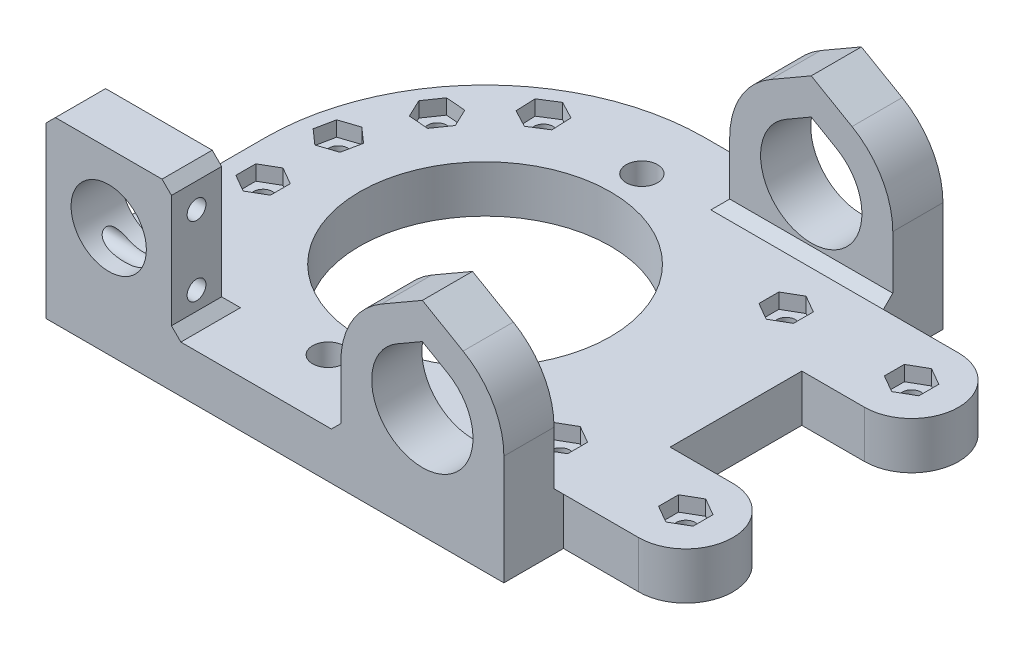
SolidWorks part; units mm, degrees
ref_plane "Front Plane" through (0, 0, 0) normal (0, 0, 1) x (1, 0, 0)
ref_plane "Top Plane" through (0, 0, 0) normal (0, 1, 0) x (1, 0, 0)
ref_plane "Right Plane" through (0, 0, 0) normal (1, 0, 0) x (0, 0, -1)
sketch "Sketch1" plane through (0, 0, 0) normal (0, 1, 0) x (1, 0, 0)
  line L0 (-62.4163, 0) -> (61.9965, 0) construction
  line L1 (-36.5, 35) -> (36.5, 35)
  line L2 (-36.5, 35) -> (-36.5, -35)
  line L3 (-36.5, -35) -> (36.5, -35)
  line L4 (36.5, 35) -> (36.5, -35) construction
  line L5 (-36.5, 35) -> (36.5, -35) construction
  line L6 (-36.5, -35) -> (36.5, 35) construction
  line L7 (36.5, 35) -> (36.5, 25.5)
  line L8 (36.5, 25.5) -> (48.5, 25.5)
  line L9 (48.5, 10.5) -> (38.5, 10.5)
  line L10 (38.5, 10.5) -> (38.5, -10.5)
  line L11 (48.5, -10.5) -> (38.5, -10.5)
  line L12 (36.5, -25.5) -> (48.5, -25.5)
  line L13 (36.5, -35) -> (36.5, -25.5)
  arc A0 (48.5, 25.5) -> (48.5, 10.5) centre (48.5, 18) cw
  arc A1 (48.5, -25.5) -> (48.5, -10.5) centre (48.5, -18) ccw
  point P0 (0, 0)
  point P15 (38.5, 0)
  dimension "D1" = 73
  dimension "D2" = 70
  dimension "D3" = 75
  dimension "D4" = 15
  dimension "D5" = 10
  dimension "D6" = 9.5
extrude "Boss-Extrude1" add sketch "Sketch1" along normal blind 7.5
sketch "Sketch3" plane through (0, 0, 35) normal (0, 0, 1) x (1, 0, 0)
  line L0 (36.5, 7.5) -> (36.5, 0) construction
  line L1 (36.5, 7.5) -> (10.5, 7.5)
  line L2 (36.5, 7.5) -> (36.5, 17.5)
  line L3 (36.5, 17.5) -> (10.5, 17.5) construction
  line L4 (10.5, 7.5) -> (10.5, 17.5)
  line L5 (-36.5, 7.5) -> (36.5, 7.5) construction
  line L6 (-36.5, 0) -> (36.5, 0) construction
  line L7 (23.5, 17.5) -> (23.5, 40.9913) construction
  line L8 (17, 28.7583) -> (23.5, 32.5111)
  line L9 (19.4625, 24.4932) -> (23.5, 26.8242)
  line L10 (17, 28.7583) -> (23.5, 17.5) construction
  line L11 (27.5375, 24.4932) -> (23.5, 26.8242)
  line L12 (30, 28.7583) -> (23.5, 32.5111)
  arc A0 (19.4625, 24.4932) -> (27.5375, 24.4932) centre (23.5, 17.5) ccw
  arc A1 (10.5, 17.5) -> (17, 28.7583) centre (23.5, 17.5) cw
  arc A2 (30, 28.7583) -> (36.5, 17.5) centre (23.5, 17.5) cw
  point P10 (23.5, 17.5)
  dimension "D3" = 16.15
  dimension "D1" = 26
  dimension "D2" = 17.5
  dimension "D4" = 120
extrude "Boss-Extrude3" add sketch "Sketch3" against normal blind 8
mirror "Mirror1" about plane through (0, 0, 0) normal (0, 0, 1) of "Boss-Extrude3"
sketch "Sketch10" plane through (0, 0, 0) normal (0, -1, 0) x (1, 0, 0)
  line L1 (-36.5, 27) -> (-16.5, 27)
  line L2 (-36.5, 27) -> (-36.5, 35)
  line L3 (-36.5, 35) -> (-16.5, 35)
  line L4 (-16.5, 27) -> (-16.5, 35)
  line L6 (-36.5, 35) -> (36.5, 35) construction
  line L7 (31.575, 35) -> (15.425, 35) construction
  point P9 (23.5, 35)
  point P14 (-26.5, 35)
  dimension "D1" = 8
  dimension "D4" = 50
extrude "Boss-Extrude4" add sketch "Sketch10" against normal offset from surface (28.5 mm away) 21 up to face at (22.7812, 7.5, -0.2031) offset beyond the face yes
sketch "Sketch11" plane through (0, 0, 35) normal (0, 0, 1) x (1, 0, 0)
  circle A0 centre (-26.5, 17.5) radius 6
  point P2 (23.5, 17.5)
  dimension "D1" = 12
  dimension "D2" = 50
extrude "Cut-Extrude6" cut sketch "Sketch11" against normal up to next
sketch "Sketch12" plane through (-36.5, 0, 0) normal (-1, 0, 0) x (0, 0, 1)
  line L0 (27, 17.5) -> (35, 17.5) construction
  line L1 (27, 28.5) -> (27, 7.5) construction
  line L2 (35, 28.5) -> (35, 0) construction
  line L3 (27, 23.5) -> (27, 11.5) construction
  circle A0 centre (31, 23.05) radius 1.5
  circle A1 centre (31, 11.95) radius 1.5
  point P12 (31, 21.55)
  point P13 (31, 13.45)
  point P14 (31, 17.5)
  dimension "D2" = 3
  dimension "D1" = 8.1
extrude "Cut-Extrude7" cut sketch "Sketch12" against normal up to next
sketch "Sketch6" plane through (0, 0, 0) normal (0, -1, 0) x (1, 0, 0)
  line L0 (-36.5, -35) -> (-36.5, 35) construction
  line L3 (-36.5, 35) -> (36.5, 35) construction
  line L5 (-20.5, 35) -> (-32.5, 35) construction
  line L6 (31.575, 35) -> (15.425, 35) construction
  line L7 (-26.5, 35) -> (23.5, 35) construction
  line L9 (-1.5, 35) -> (-1.5, 0) construction
  circle A0 centre (-1.5, 0) radius 20
  point P3 (-26.5, 35)
  point P5 (-36.5, 0)
  point P10 (23.5, 35)
  point P18 (-1.5, 35)
  dimension "D1" = 40
extrude "Cut-Extrude3" cut sketch "Sketch6" against normal through all
sketch "Sketch15" plane through (0, 0, 0) normal (0, -1, 0) x (1, 0, 0)
  line L0 (-1.5, 35) -> (-1.5, -35) construction
  line L1 (-36.5, 35) -> (36.5, 35) construction
  line L2 (36.5, -35) -> (-36.5, -35) construction
  line L3 (-21.5, 0) -> (18.5, 0) construction
  circle A1 centre (-1.5, 0) radius 20 construction
  circle A2 centre (-1.5, 25) radius 2.5
  circle A3 centre (-1.5, -25) radius 2.5
  point P8 (-1.5, 0)
  dimension "D1" = 5
  dimension "D2" = 25
extrude "Cut-Extrude9" cut sketch "Sketch15" against normal through all
sketch "Sketch14" plane through (0, 0, 0) normal (0, -1, 0) x (1, 0, 0)
  line L0 (0, 0) -> (89.7656, 0) construction
  line L1 (38.5, -10.5) -> (38.5, -25.5333) construction
  circle A0 centre (48.5, -18) radius 1.5
  circle A1 centre (28.5, -18) radius 1.5
  circle A2 centre (48.5, 18) radius 1.5
  circle A3 centre (28.5, 18) radius 1.5
  dimension "D1" = 3
  dimension "D2" = 20
extrude "Cut-Extrude8" cut sketch "Sketch14" against normal through all
sketch "Sketch19" plane through (0, 7.5, 0) normal (0, 1, 0) x (1, 0, 0)
  line L0 (38.5, 0) -> (82.8981, 0) construction
  line L1 (38.5, -10.5) -> (38.5, 10.5) construction
  line L2 (28.5, -18) -> (48.5, -18) construction
  line L3 (38.5, -18) -> (38.5, 0) construction
  line L4 (25.75, -16.4123) -> (28.5, -14.8246)
  line L5 (48.5, -14.8246) -> (45.75, -16.4123)
  line L6 (45.75, -16.4123) -> (45.75, -19.5877)
  line L7 (45.75, -19.5877) -> (48.5, -21.1754)
  line L8 (48.5, -21.1754) -> (51.25, -19.5877)
  line L9 (51.25, -19.5877) -> (51.25, -16.4123)
  line L10 (51.25, -16.4123) -> (48.5, -14.8246)
  line L11 (25.75, -19.5877) -> (25.75, -16.4123)
  line L12 (28.5, -21.1754) -> (25.75, -19.5877)
  line L13 (31.25, -19.5877) -> (28.5, -21.1754)
  line L14 (31.25, -16.4123) -> (31.25, -19.5877)
  line L15 (28.5, -14.8246) -> (31.25, -16.4123)
  line L16 (48.5, 21.1754) -> (51.25, 19.5877)
  line L17 (45.75, 19.5877) -> (48.5, 21.1754)
  line L18 (51.25, 16.4123) -> (48.5, 14.8246)
  line L19 (51.25, 19.5877) -> (51.25, 16.4123)
  line L20 (45.75, 16.4123) -> (45.75, 19.5877)
  line L21 (48.5, 14.8246) -> (45.75, 16.4123)
  line L22 (28.5, 14.8246) -> (31.25, 16.4123)
  line L23 (31.25, 16.4123) -> (31.25, 19.5877)
  line L24 (31.25, 19.5877) -> (28.5, 21.1754)
  line L25 (28.5, 21.1754) -> (25.75, 19.5877)
  line L26 (25.75, 19.5877) -> (25.75, 16.4123)
  line L27 (25.75, 16.4123) -> (28.5, 14.8246)
  circle A0 centre (48.5, -18) radius 2.75 construction
  circle A1 centre (48.5, 18) radius 2.75 construction
  dimension "D1" = 5.5
extrude "Cut-Extrude13" cut sketch "Sketch19" against normal blind 2.4
fillet "Fillet2" radius 35 1 edges at (-36.5, 3.75, -35)
chamfer "Chamfer2" distance 1.5 angle 45 8 edges at (-16.5, 28.5, 31) (-36.5, 28.5, 31) (-26.5, 7.5, 27) (-16.5, 7.5, 31) (23.5, 7.5, -27) (10.5, 7.5, -31)
sketch "Sketch17" plane through (0, 0, 0) normal (0, -1, 0) x (1, 0, 0)
  line L0 (-1.5, 0) -> (-36.5, 0) construction
  line L1 (-1.5, 0) -> (-16.5, -25.9808) construction
  line L2 (-1.5, 0) -> (-27.4808, 15) construction
  line L3 (-26.1909, 17.04) -> (-30.8939, 6) construction
  line L4 (-30.8939, 6) -> (-30.8939, -6) construction
  line L5 (-30.8939, -6) -> (-26.1909, -17.04) construction
  line L6 (-26.1909, -17.04) -> (-17.5373, -25.3536) construction
  line L7 (-30.8939, 6) -> (-30.8939, 18) construction
  circle A0 centre (-1.5, 0) radius 30 construction
  circle A1 centre (-30.8939, 6) radius 1.5
  circle A2 centre (-30.8939, -6) radius 1.5
  circle A3 centre (-30.8939, 18) radius 1.5
  circle A4 centre (-26.1909, -17.04) radius 1.5
  circle A5 centre (-17.5373, -25.3536) radius 1.5
  point P0 (-1.5, 0)
  point P5 (-31.5, 0)
  dimension "D2" = 60
  dimension "D5" = 3
  dimension "D1" = 30
  dimension "D3" = 5
  dimension "D4" = 12
extrude "Cut-Extrude11" cut sketch "Sketch17" against normal up to next
sketch "Sketch18" plane through (0, 7.5, 0) normal (0, 1, 0) x (1, 0, 0)
  line L0 (-30.8939, -18) -> (-1.5, 0) construction
  line L1 (-28.1439, -19.5877) -> (-28.1439, -16.4123)
  line L2 (-28.1439, -16.4123) -> (-30.8939, -14.8246)
  line L3 (-30.8939, -14.8246) -> (-33.6439, -16.4123)
  line L4 (-33.6439, -16.4123) -> (-33.6439, -19.5877)
  line L5 (-33.6439, -19.5877) -> (-30.8939, -21.1754)
  line L6 (-30.8939, -21.1754) -> (-28.1439, -19.5877)
  line L7 (-28.1439, -4.4123) -> (-30.8939, -2.8246)
  line L8 (-30.8939, -2.8246) -> (-33.6439, -4.4123)
  line L9 (-33.6439, -4.4123) -> (-33.6439, -7.5877)
  line L10 (-33.6439, -7.5877) -> (-30.8939, -9.1754)
  line L11 (-30.8939, -9.1754) -> (-28.1439, -7.5877)
  line L12 (-28.1439, -7.5877) -> (-28.1439, -4.4123)
  line L13 (-27.8819, 7.0056) -> (-30.2588, 9.1113)
  line L14 (-30.2588, 9.1113) -> (-33.2708, 8.1056)
  line L15 (-33.2708, 8.1056) -> (-33.9059, 4.9944)
  line L16 (-33.9059, 4.9944) -> (-31.529, 2.8887)
  line L17 (-31.529, 2.8887) -> (-28.517, 3.8944)
  line L18 (-28.517, 3.8944) -> (-27.8819, 7.0056)
  line L19 (-23.0257, 16.7847) -> (-24.3872, 19.6535)
  line L20 (-24.3872, 19.6535) -> (-27.5524, 19.9087)
  line L21 (-27.5524, 19.9087) -> (-29.356, 17.2953)
  line L22 (-29.356, 17.2953) -> (-27.9945, 14.4265)
  line L23 (-27.9945, 14.4265) -> (-24.8293, 14.1713)
  line L24 (-24.8293, 14.1713) -> (-23.0257, 16.7847)
  line L25 (-14.7254, 23.8783) -> (-14.8537, 27.0511)
  line L26 (-14.8537, 27.0511) -> (-17.6656, 28.5264)
  line L27 (-17.6656, 28.5264) -> (-20.3492, 26.8289)
  line L28 (-20.3492, 26.8289) -> (-20.2209, 23.6561)
  line L29 (-20.2209, 23.6561) -> (-17.409, 22.1808)
  line L30 (-17.409, 22.1808) -> (-14.7254, 23.8783)
  line L31 (-1.5, 0) -> (-30.8939, -6) construction
  line L32 (-1.5, 0) -> (-30.8939, 6) construction
  line L33 (-1.5, 0) -> (-26.1909, 17.04) construction
  line L34 (-1.5, 0) -> (-17.5373, 25.3536) construction
  line L35 (-36.5, 0) -> (-36.5, -35) construction
  circle A0 centre (-30.8939, -18) radius 2.75 construction
  circle A1 centre (-30.8939, -6) radius 2.75 construction
  circle A2 centre (-30.8939, 6) radius 2.75 construction
  circle A3 centre (-26.1909, 17.04) radius 2.75 construction
  circle A4 centre (-17.5373, 25.3536) radius 2.75 construction
  point P0 (-30.8939, -18)
  point P1 (-30.8939, -6)
  point P3 (-30.8939, 6)
  point P5 (-26.1909, 17.04)
  point P7 (-17.5373, 25.3536)
  point P43 (-1.5, 0)
  point P55 (-30.8939, -18)
  dimension "D1" = 5.5
extrude "Cut-Extrude12" cut sketch "Sketch18" against normal blind 2.4
move or copy body "Body-Move/Copy1" [suppressed] bodies to move or copy 119 copy no rotation origin (0, 15.25, 0) rotation axis (1, 0, 0) rotation angle 90
